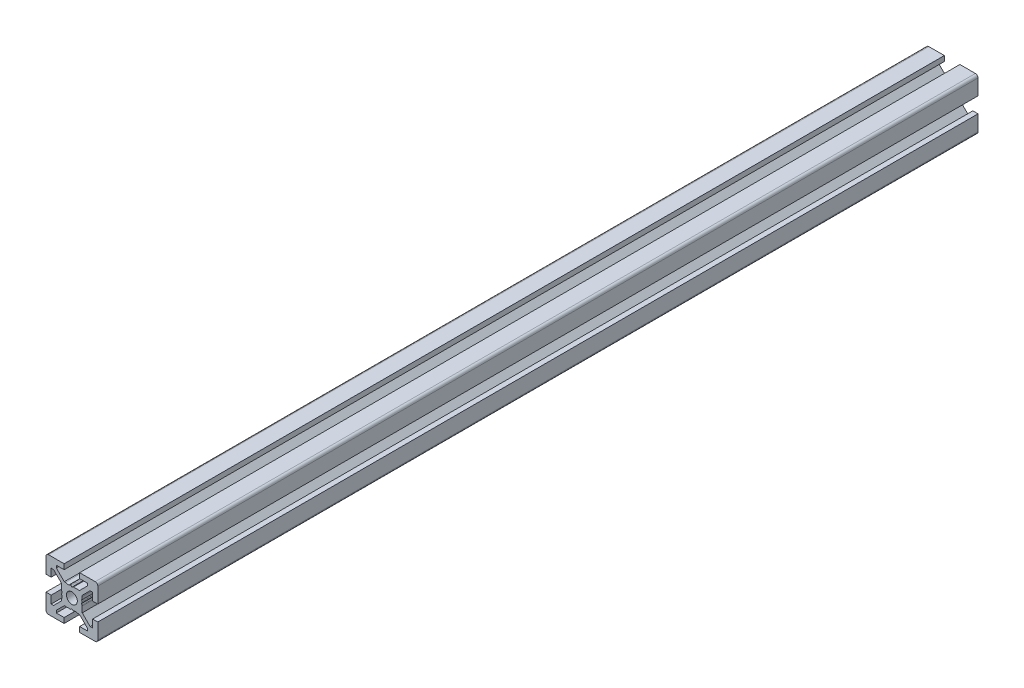
SolidWorks part; units mm, degrees
ref_plane "Front Plane" through (0, 0, 0) normal (0, 0, 1) x (1, 0, 0)
ref_plane "Top Plane" through (0, 0, 0) normal (0, 1, 0) x (1, 0, 0)
ref_plane "Right Plane" through (0, 0, 0) normal (1, 0, 0) x (0, 0, -1)
ref_plane "Plane1" through (0, 0, -2000) normal (0, 0, -1) x (-1, 0, 0)
sketch "Sketch1" plane through (0, 0, -2000) normal (0, 0, -1) x (-1, 0, 0)
  line L0 (10, -3) -> (8, -3)
  line L1 (8, -3) -> (8, -6)
  line L2 (8, -6) -> (7.0607, -6)
  line L3 (7.0607, -6) -> (4, -2.9393)
  line L4 (4, -2.9393) -> (4, -2.5)
  line L5 (4, -2.5) -> (3.751, -1.2189)
  line L6 (3.751, -1.2189) -> (3.933, -0.9036)
  line L7 (3.933, -0.4036) -> (3.7, 0)
  line L8 (3.7, 0) -> (3.933, 0.4036)
  line L9 (4, 0.6536) -> (4, 2.9393)
  line L10 (4, 2.9393) -> (7.0607, 6)
  line L11 (7.0607, 6) -> (8, 6)
  line L12 (8, 6) -> (8, 3)
  line L13 (8, 3) -> (10, 3)
  line L14 (10, 3) -> (10, 9)
  line L15 (9, 10) -> (3, 10)
  line L16 (3, 10) -> (3, 8)
  line L17 (3, 8) -> (6, 8)
  line L18 (6, 8) -> (6, 7.0607)
  line L19 (6, 7.0607) -> (2.9393, 4)
  line L20 (2.9393, 4) -> (2.5, 4)
  line L21 (2.5, 4) -> (1.2189, 3.751)
  line L22 (1.2189, 3.751) -> (0.9036, 3.933)
  line L23 (0.4036, 3.933) -> (0, 3.7)
  line L24 (0, 3.7) -> (-0.4036, 3.933)
  line L25 (-0.6536, 4) -> (-2.9393, 4)
  line L26 (-2.9393, 4) -> (-6, 7.0607)
  line L27 (-6, 7.0607) -> (-6, 8)
  line L28 (-6, 8) -> (-3, 8)
  line L29 (-3, 8) -> (-3, 10)
  line L30 (-3, 10) -> (-9, 10)
  line L31 (-10, 9) -> (-10, 3)
  line L32 (-10, 3) -> (-8, 3)
  line L33 (-8, 3) -> (-8, 6)
  line L34 (-8, 6) -> (-7.0607, 6)
  line L35 (-7.0607, 6) -> (-4, 2.9393)
  line L36 (-4, 2.9393) -> (-4, 2.5)
  line L37 (-4, 2.5) -> (-3.751, 1.2189)
  line L38 (-3.751, 1.2189) -> (-3.933, 0.9036)
  line L39 (-3.933, 0.4036) -> (-3.7, 0)
  line L40 (-3.7, 0) -> (-3.933, -0.4036)
  line L41 (-4, -0.6536) -> (-4, -2.9393)
  line L42 (-4, -2.9393) -> (-7.0607, -6)
  line L43 (-7.0607, -6) -> (-8, -6)
  line L44 (-8, -6) -> (-8, -3)
  line L45 (-8, -3) -> (-10, -3)
  line L46 (-10, -3) -> (-10, -9)
  line L47 (-9, -10) -> (-3, -10)
  line L48 (-3, -10) -> (-3, -8)
  line L49 (-3, -8) -> (-6, -8)
  line L50 (-6, -8) -> (-6, -7.0607)
  line L51 (-6, -7.0607) -> (-2.9393, -4)
  line L52 (-2.9393, -4) -> (-2.5, -4)
  line L53 (-2.5, -4) -> (-1.2189, -3.751)
  line L54 (-1.2189, -3.751) -> (-0.9036, -3.933)
  line L55 (-0.4036, -3.933) -> (0, -3.7)
  line L56 (0, -3.7) -> (0.4036, -3.933)
  line L57 (0.6536, -4) -> (2.9393, -4)
  line L58 (2.9393, -4) -> (6, -7.0607)
  line L59 (6, -7.0607) -> (6, -8)
  line L60 (6, -8) -> (3, -8)
  line L61 (3, -8) -> (3, -10)
  line L62 (3, -10) -> (9, -10)
  line L63 (10, -9) -> (10, -3)
  circle A0 centre (0, 0) radius 2.1
  arc A1 (3.933, -0.9036) -> (3.933, -0.4036) centre (3.5, -0.6536) ccw
  arc A2 (3.933, 0.4036) -> (4, 0.6536) centre (3.5, 0.6536) ccw
  arc A3 (10, 9) -> (9, 10) centre (9, 9) ccw
  arc A4 (0.9036, 3.933) -> (0.4036, 3.933) centre (0.6536, 3.5) ccw
  arc A5 (-0.4036, 3.933) -> (-0.6536, 4) centre (-0.6536, 3.5) ccw
  arc A6 (-9, 10) -> (-10, 9) centre (-9, 9) ccw
  arc A7 (-3.933, 0.9036) -> (-3.933, 0.4036) centre (-3.5, 0.6536) ccw
  arc A8 (-3.933, -0.4036) -> (-4, -0.6536) centre (-3.5, -0.6536) ccw
  arc A9 (-10, -9) -> (-9, -10) centre (-9, -9) ccw
  arc A10 (-0.9036, -3.933) -> (-0.4036, -3.933) centre (-0.6536, -3.5) ccw
  arc A11 (0.4036, -3.933) -> (0.6536, -4) centre (0.6536, -3.5) ccw
  arc A12 (9, -10) -> (10, -9) centre (9, -9) ccw
extrude "Boss-Extrude1" add sketch "Sketch1" against normal blind 340
